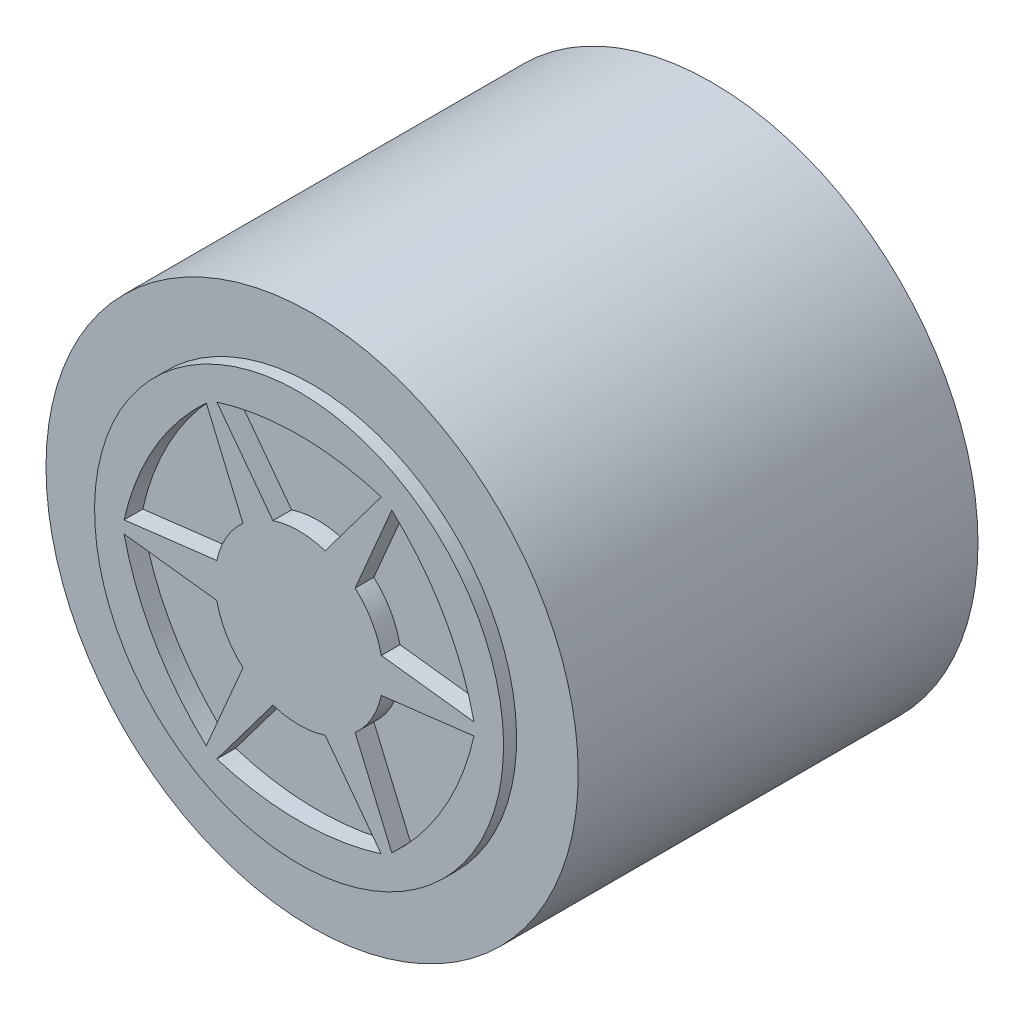
SolidWorks part; units mm, degrees
ref_plane "Alzado" through (0, 0, 0) normal (0, 0, 1) x (1, 0, 0)
ref_plane "Planta" through (0, 0, 0) normal (0, 1, 0) x (1, 0, 0)
ref_plane "Vista lateral" through (0, 0, 0) normal (1, 0, 0) x (0, 0, -1)
sketch "Croquis1" plane through (0, 0, 0) normal (1, 0, 0) x (0, 0, -1)
  line L0 (0, 0) -> (9.25, 0)
  line L1 (0, 0) -> (-12.95, 0)
  line L2 (-12.95, 0) -> (-12.95, 10.95)
  line L3 (-12.95, 10.95) -> (-12.25, 10.95)
  line L4 (-12.25, 10.95) -> (-12.25, 10.25)
  line L5 (-12.25, 10.25) -> (9.25, 10.25)
  line L14 (9.25, 10.25) -> (9.25, 0)
  dimension "D1" = 10.25
  dimension "D2" = 10.95
  dimension "D3" = 0.7
  dimension "D4" = 21.5
  dimension "D8" = 12.95
revolve "Revolución1" add sketch "Croquis1" angle 360 about L1
ref_plane "Plano1" through (0, 0, 12.95) normal (0, 0, 1) x (1, 0, 0)
sketch "Croquis5" plane through (0, 0, 12.95) normal (0, 0, 1) x (1, 0, 0)
  line L0 (0, 0) -> (0, 9.0083) construction
  line L1 (1.4, 4.2767) -> (4.4, 8.2767)
  line L2 (-1.4, 4.2767) -> (-4.4, 8.2767)
  line L3 (0, 8.95) -> (0, 10.95) construction
  line L4 (4.4037, 0.9259) -> (9.3678, 0.3278)
  line L5 (3.0037, 3.3508) -> (4.9678, 7.9489)
  line L6 (3.0037, -3.3508) -> (4.9678, -7.9489)
  line L7 (4.4037, -0.9259) -> (9.3678, -0.3278)
  line L8 (-1.4, -4.2767) -> (-4.4, -8.2767)
  line L9 (1.4, -4.2767) -> (4.4, -8.2767)
  line L10 (-4.4037, -0.9259) -> (-9.3678, -0.3278)
  line L11 (-3.0037, -3.3508) -> (-4.9678, -7.9489)
  line L12 (-3.0037, 3.3508) -> (-4.9678, 7.9489)
  line L13 (-4.4037, 0.9259) -> (-9.3678, 0.3278)
  circle A0 centre (0, 0) radius 4.5
  circle A1 centre (0, 0) radius 10.95 construction
  arc A2 (4.9678, 7.9489) -> (9.3678, 0.3278) centre (-4.9911, -2.8816) cw
  arc A3 (-4.4, 8.2767) -> (4.4, 8.2767) centre (0, -5.7632) cw
  arc A4 (9.3678, -0.3278) -> (4.9678, -7.9489) centre (-4.9911, 2.8816) cw
  arc A5 (4.4, -8.2767) -> (-4.4, -8.2767) centre (0, 5.7632) cw
  arc A6 (-4.9678, -7.9489) -> (-9.3678, -0.3278) centre (4.9911, 2.8816) cw
  arc A7 (-9.3678, 0.3278) -> (-4.9678, 7.9489) centre (4.9911, -2.8816) cw
  point P41 (0, 0)
  dimension "D1" = 9
  dimension "D2" = 1.4
  dimension "D5" = 3
  dimension "D6" = 5
  dimension "D4" = 6
extrude "Cortar-Extruir4" cut sketch "Croquis5" against normal blind 1 contours A3 L2 A0 L1 | A2 L5 A0 L4 | A4 L7 A0 L6 | A5 L9 A0 L8 | A6 L11 A0 L10 | A7 L13 A0 L12
sketch "Croquis7" plane through (0, 0, -9.25) normal (0, 0, -1) x (-1, 0, 0)
  circle A0 centre (0, 0) radius 7.5
  dimension "D1" = 15
extrude "Cortar-Extruir5" cut sketch "Croquis7" against normal blind 9
sketch "Croquis8" plane through (0, 0, -0.25) normal (0, 0, -1) x (-1, 0, 0)
  line L0 (-1.1402, -1.05) -> (1.1402, -1.05)
  arc A0 (1.1402, -1.05) -> (-1.1402, -1.05) centre (0, 0) ccw
  dimension "D1" = 3.1
  dimension "D2" = 1.05
extrude "Cortar-Extruir6" cut sketch "Croquis8" against normal blind 9
ref_plane "Plano2" through (0, -11.25, 0) normal (0, 1, 0) x (1, 0, 0)
sketch "Croquis10" plane through (0, -11.25, 0) normal (0, 1, 0) x (1, 0, 0)
  line L0 (10.95, -12.25) -> (-10.95, -12.25) construction
  circle A0 centre (0, -5.75) radius 3
  dimension "D2" = 6
  dimension "D1" = 6.5
extrude "Cortar-Extruir8" cut sketch "Croquis10" along normal blind 5 and the other way through all
sketch "Croquis11" plane through (0, -6.25, 0) normal (0, -1, 0) x (1, 0, 0)
  circle A0 centre (0, 5.75) radius 1.5
  dimension "D1" = 3
extrude "Cortar-Extruir9" cut sketch "Croquis11" against normal up to surface (5.2 mm away) up to face at (0, -1.05, 4.25)
sketch "Croquis12" plane through (0, 0, 0) normal (1, 0, 0) x (0, 0, -1)
  line L0 (-12.25, 10.25) -> (-12.25, 14.25)
  line L1 (-12.25, 14.25) -> (9.1565, 14.25)
  line L2 (9.1565, 14.25) -> (9.25, 10.25)
  line L3 (9.25, 10.25) -> (-12.25, 10.25)
  line L4 (0, 0) -> (16.3228, 0) construction
  dimension "D1" = 4
revolve "Revolución3" add sketch "Croquis12" angle 360 about L4
